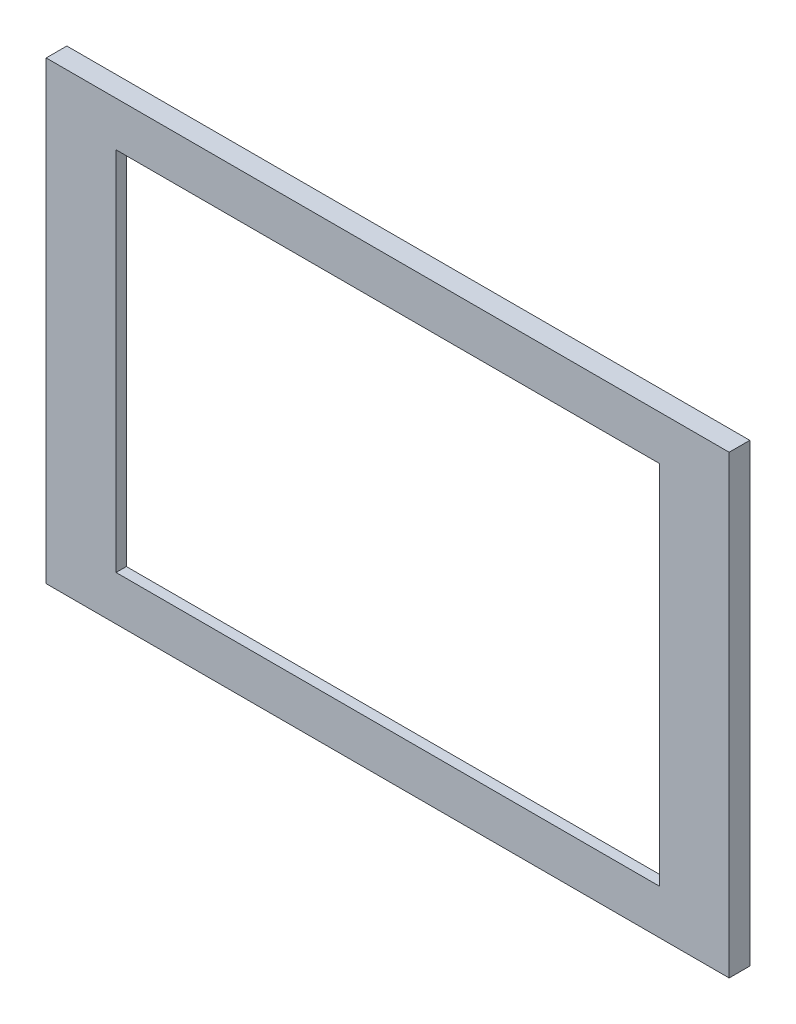
SolidWorks part; units mm, degrees
ref_plane "Front Plane" through (0, 0, 0) normal (0, 0, 1) x (1, 0, 0)
ref_plane "Top Plane" through (0, 0, 0) normal (0, 1, 0) x (1, 0, 0)
ref_plane "Right Plane" through (0, 0, 0) normal (1, 0, 0) x (0, 0, -1)
sketch "Sketch1" plane through (0, 0, 0) normal (0, 0, 1) x (1, 0, 0)
  line L0 (-10.5, -50.24) -> (-10.5, -56.04)
  line L1 (-41.76, -28.14) -> (41.76, -28.14)
  line L2 (-41.76, -28.14) -> (-41.76, 28.14)
  line L3 (-41.76, 28.14) -> (41.76, 28.14)
  line L4 (41.76, -28.14) -> (41.76, 28.14)
  line L5 (-41.76, -28.14) -> (41.76, 28.14) construction
  line L6 (-41.76, 28.14) -> (41.76, -28.14) construction
  line L7 (-56.76, 43.14) -> (56.76, 43.14)
  line L8 (-56.76, 43.14) -> (-56.76, -68.14)
  line L9 (-56.76, -68.14) -> (56.76, -68.14)
  line L10 (56.76, 43.14) -> (56.76, -68.14)
  line L11 (-25.5, -50.24) -> (-19.5, -50.24)
  line L12 (-25.5, -50.24) -> (-25.5, -56.04)
  line L13 (-25.5, -56.04) -> (-19.5, -56.04)
  line L14 (-19.5, -50.24) -> (-19.5, -56.04)
  line L15 (-41.76, -53.14) -> (41.76, -53.14) construction
  line L16 (-10.5, -50.24) -> (-4.5, -50.24)
  line L17 (-4.5, -50.24) -> (-4.5, -56.04)
  line L18 (-10.5, -56.04) -> (-4.5, -56.04)
  line L19 (4.5, -50.24) -> (4.5, -56.04)
  line L20 (4.5, -50.24) -> (10.5, -50.24)
  line L21 (10.5, -50.24) -> (10.5, -56.04)
  line L22 (4.5, -56.04) -> (10.5, -56.04)
  line L23 (19.5, -50.24) -> (19.5, -56.04)
  line L24 (19.5, -50.24) -> (25.5, -50.24)
  line L25 (25.5, -50.24) -> (25.5, -56.04)
  line L26 (19.5, -56.04) -> (25.5, -56.04)
  line L27 (-4.5, -53.14) -> (4.5, -53.14) construction
  line L28 (0, -68.14) -> (0, -53.44) construction
  line L29 (-4.5, -53.14) -> (4.5, -53.14) construction
  circle A0 centre (-41.76, -53.14) radius 8.5
  circle A1 centre (41.76, -53.14) radius 8.5
  point P0 (0, 0)
  point P16 (-25.5, -53.14)
  dimension "D12" = 17
  dimension "D13" = 17
  dimension "D1" = 56.28
  dimension "D2" = 83.52
  dimension "D3" = 15
  dimension "D4" = 15
  dimension "D5" = 113.52
  dimension "D6" = 15
  dimension "D7" = 40
  dimension "D8" = 15
  dimension "D9" = 15
  dimension "D10" = 15
  dimension "D11" = 15
  dimension "D14" = 6
  dimension "D15" = 5.8
  dimension "D16" = 4
extrude "Boss-Extrude1" add sketch "Sketch1" along normal blind 3.175
sketch "Sketch3" plane through (0, 0, 0) normal (0, 0, -1) x (-1, 0, 0)
  line L0 (41.76, 28.14) -> (41.76, -28.14) construction
  line L1 (41.76, -28.14) -> (-41.76, -28.14) construction
  line L2 (-41.76, -28.14) -> (-41.76, 28.14) construction
  line L3 (-41.76, 28.14) -> (41.76, 28.14) construction
  line L4 (41.76, 28.14) -> (41.76, -28.14)
  line L5 (41.76, -28.14) -> (-41.76, -28.14)
  line L6 (-41.76, -28.14) -> (-41.76, 28.14)
  line L7 (-41.76, 28.14) -> (41.76, 28.14)
  line L9 (-47.385, 30.54) -> (49.26, 30.54)
  line L10 (-47.385, 30.54) -> (-47.385, -30.54)
  line L11 (-47.385, -30.54) -> (49.26, -30.54)
  line L12 (49.26, 30.54) -> (49.26, -30.54)
  point P2 (0, 0)
  point P12 (45.71, 30.54)
  dimension "D1" = 5.625
  dimension "D2" = 61.08
  dimension "D3" = 7.5
  dimension "D4" = 2.4
  dimension "D5" = 96.645
  dimension "D6" = 83.52
extrude "Cut-Extrude1" cut sketch "Sketch3" against normal blind 1.5875
sketch "Sketch4" plane through (0, 0, 3.175) normal (0, 0, 1) x (1, 0, 0)
  line L1 (-52.5, 35) -> (52.5, 35)
  line L2 (-52.5, 35) -> (-52.5, -35)
  line L3 (-52.5, -35) -> (52.5, -35)
  line L4 (52.5, 35) -> (52.5, -35)
  line L5 (-52.5, 35) -> (52.5, -35) construction
  line L6 (-52.5, -35) -> (52.5, 35) construction
  line L10 (-56.76, 43.14) -> (-56.76, -68.14)
  line L11 (-56.76, -68.14) -> (56.76, -68.14)
  line L12 (56.76, -68.14) -> (56.76, 43.14)
  line L13 (56.76, 43.14) -> (-56.76, 43.14)
  line L14 (-56.76, 43.14) -> (-56.76, -68.14)
  line L15 (-56.76, -68.14) -> (56.76, -68.14)
  line L16 (56.76, -68.14) -> (56.76, 43.14)
  line L17 (56.76, 43.14) -> (-56.76, 43.14)
  point P0 (0, 0)
  dimension "D1" = 105
  dimension "D2" = 70
  dimension "D3" = 0
extrude "Cut-Extrude2" cut sketch "Sketch4" along direction (0, 0, 1) on the side against the normal blind 10
